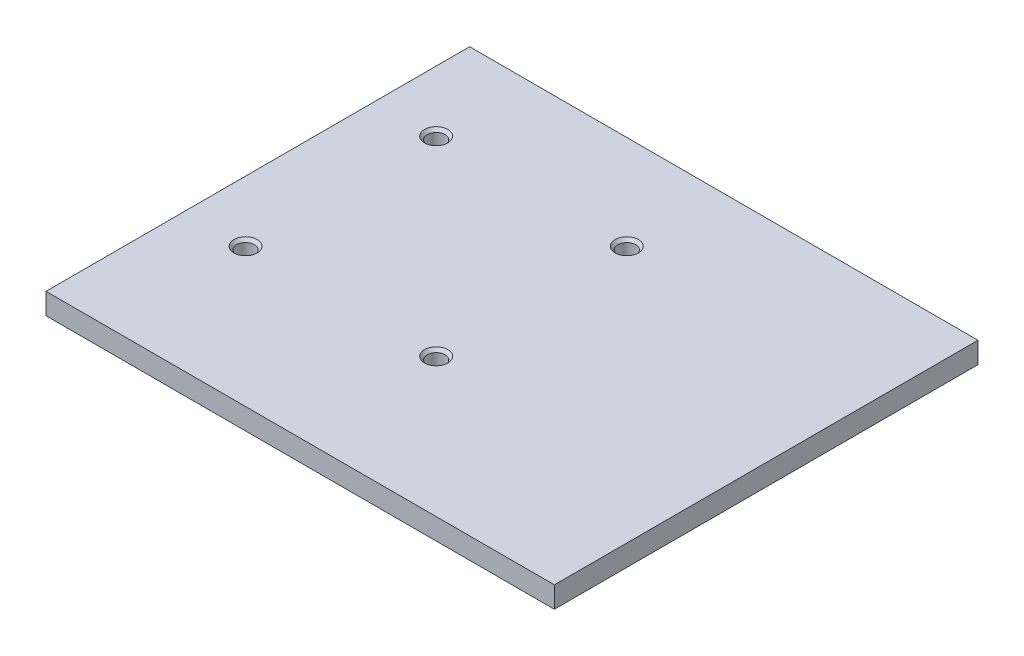
SolidWorks part; units mm, degrees
ref_plane "Front Plane" through (0, 0, 0) normal (0, 0, 1) x (1, 0, 0)
ref_plane "Top Plane" through (0, 0, 0) normal (0, 1, 0) x (1, 0, 0)
ref_plane "Right Plane" through (0, 0, 0) normal (1, 0, 0) x (0, 0, -1)
sketch "Sketch1" plane through (0, 0, 0) normal (0, 1, 0) x (1, 0, 0)
  line L0 (-152.4, 127) -> (152.4, -127) construction
  line L1 (-152.4, 127) -> (152.4, 127)
  line L2 (-152.4, 127) -> (-152.4, -127)
  line L3 (-152.4, -127) -> (152.4, -127)
  line L4 (152.4, 127) -> (152.4, -127)
  dimension "D1" = 254
  dimension "D2" = 304.8
extrude "Boss-Extrude1" add sketch "Sketch1" along normal blind 12.7
hole_wizard "1/2-13 Tapped Hole1" positions "Sketch2" profile "Sketch3" tap size "1/2-13" standard "ANSI Inch" end condition up to next
sketch "Sketch2" plane through (0, 12.7, 0) normal (0, 1, 0) x (1, 0, 0)
  point P0 (-115.9795, 70.5189)
  point P3 (-1.6795, 70.5189)
  point P6 (-1.6795, -43.7811)
  point P9 (-115.9795, -43.7811)
sketch "Sketch3" plane through (-115.9795, 12.7, -70.5189) normal (1, 0, 0) x (0, 0, 1)
  line L0 (0, 0) -> (0, 12.7)
  line L1 (0, 12.7) -> (5.3581, 12.7)
  line L2 (5.3581, 12.7) -> (5.3581, 1.8715)
  line L3 (5.3581, 1.8715) -> (6.985, 0)
  line L5 (6.985, 0) -> (0, 0)
  line L6 (-5.3581, 1.8715) -> (-6.985, 0) construction
  line L11 (0, -6.35) -> (0, 107.95) construction
  dimension "Thru Tap Drill Dia." = 10.7163
  dimension "Thru Tap Drill Depth" = 12.7
  dimension "Near C'Sink Dia." = 13.97
  dimension "Near C'Sink Angle" = 82
cosmetic thread "Hole Thread1" parameters "D2"=12.7
cosmetic thread "Hole Thread2" parameters "D2"=12.7
cosmetic thread "Hole Thread3" parameters "D2"=12.7
cosmetic thread "Hole Thread4" parameters "D2"=12.7
